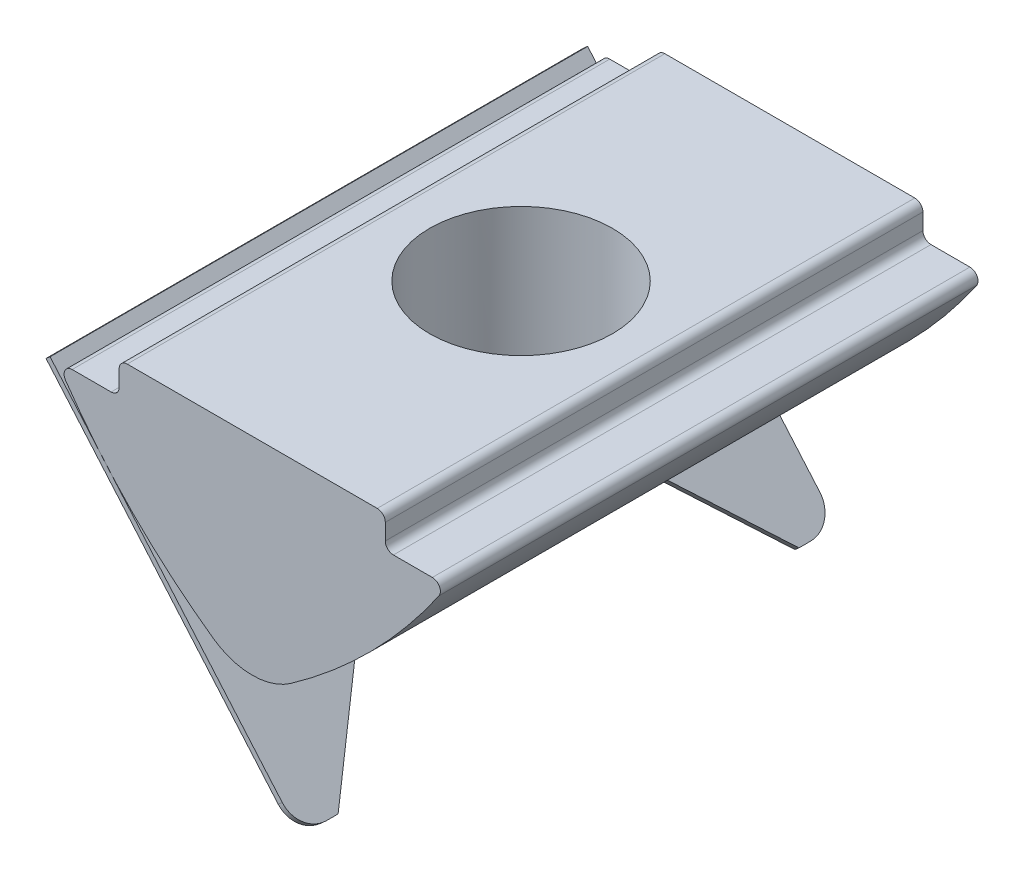
SolidWorks part; units mm, degrees
ref_plane "前视基准面" through (0, 0, 0) normal (0, 0, 1) x (1, 0, 0)
ref_plane "上视基准面" through (0, 0, 0) normal (0, 1, 0) x (1, 0, 0)
ref_plane "右视基准面" through (0, 0, 0) normal (1, 0, 0) x (0, 0, -1)
sketch "草图1" plane through (0, 0, 0) normal (0, 0, 1) x (1, 0, 0)
  line B0 (-4.95, -0.3) -> (-4.95, -0.9)
  line B1 (4.95, -0.3) -> (4.95, -0.9)
  line B2 (4.65, 0) -> (-4.65, 0)
  line B3 (-5.25, -1.2) -> (-6.7, -1.2)
  line B4 (5.25, -1.2) -> (6.7, -1.2)
  arc B5 (4.95, -0.3) -> (4.65, 0) centre (4.65, -0.3) ccw
  arc B6 (-4.65, 0) -> (-4.95, -0.3) centre (-4.65, -0.3) ccw
  arc B7 (-5.25, -1.2) -> (-4.95, -0.9) centre (-5.25, -0.9) ccw
  arc B8 (4.95, -0.9) -> (5.25, -1.2) centre (5.25, -0.9) ccw
  arc B9 (-1.4566, -7.2318) -> (1.4566, -7.2318) centre (0, -5.2) ccw
  arc B10 (1.4276, -7.2523) -> (6.9516, -1.6634) centre (-11.418, 10.9685) ccw
  arc B11 (6.9516, -1.6634) -> (6.7, -1.2) centre (6.7, -1.5) ccw
  arc B12 (-6.9516, -1.6634) -> (-1.4276, -7.2523) centre (11.418, 10.9685) ccw
  arc B13 (-6.7, -1.2) -> (-6.9516, -1.6634) centre (-6.7, -1.5) ccw
sketch_block_instance "A$C525F5C17-1"
sketch_block "A$C525F5C17"
extrude "凸台-拉伸1" add sketch "草图1" along normal mid plane 20 contours B3 B13 B12 B9 B10 B11 B4 B8 B1 B5 B2 B6 B0 B7
sketch "草图3" plane through (0, 0, 0) normal (0, 1, 0) x (1, 0, 0)
  point P0 (0, 0)
hole_wizard "M8 螺纹孔1" positions "3D草图2" profile "草图4" tap size "M8" standard "Iso"
sketch3d "3D草图2"
  point P0 (0, 0, 0)
sketch "草图4" plane through (0, 0, 0) normal (1, 0, 0) x (0, 0, 1)
  line L0 (0, 0) -> (0, 21.7929)
  line L1 (0, 21.7929) -> (3.4, 19.75)
  line L2 (3.4, 19.75) -> (3.4, 0)
  line L5 (3.4, 0) -> (0, 0)
  line L10 (0, 21.7929) -> (-3.4, 19.75) construction
  line L11 (0, -6.35) -> (0, 107.95) construction
  dimension "螺纹孔钻头直径" = 6.8
  dimension "螺纹孔钻头深度" = 19.75
  dimension "导头角度" = 118
cosmetic thread "孔螺蚊线1" parameters "D1"=7.7, "D2"=8
sketch "草图5" plane through (0, 0, 10) normal (0, 0, 1) x (1, 0, 0)
  line L0 (-7.5212, -1.2) -> (1.7673, -12)
  line L1 (4.65, 0) -> (-4.65, 0) construction
  line L2 (-7.6728, -1.3304) -> (1.6157, -12.1304)
  line L4 (-7.5212, -1.2) -> (-7.6728, -1.3304)
  line L5 (1.7673, -12) -> (1.6157, -12.1304)
  arc A1 (-6.9516, -1.6634) -> (-1.4276, -7.2523) centre (11.418, 10.9685) ccw construction
  dimension "D1" = 12
  dimension "D2" = 0.2
extrude "凸台-拉伸2" add sketch "草图5" against normal blind 20 separate body
sketch "草图6" plane through (-5.0682, -4.3589, 0) normal (-0.7582, -0.6521, 0) x (0, 0, 1)
  line L0 (-1.5674, -3.0135) -> (1.5674, -3.0135)
  line L1 (0, 0) -> (0, -3.0135) construction
  line L2 (3.0995, -3.7279) -> (8.5725, -10.2504)
  line L3 (-10, -10.2504) -> (10, -10.2504) construction
  line L4 (8.5725, -10.2504) -> (9, -10.2504)
  line L5 (10, -9.2504) -> (10, -6.703)
  line L6 (-10, -9.2504) -> (-10, -6.703)
  line L7 (-8.5725, -10.2504) -> (-9, -10.2504)
  line L8 (-3.0995, -3.7279) -> (-8.5725, -10.2504)
  line L9 (10, -6.703) -> (14.4576, -13.4188)
  line L10 (14.4576, -13.4188) -> (-1.0667, -21.0252)
  line L11 (-1.0667, -21.0252) -> (-16.3104, -17.222)
  line L12 (-16.3104, -17.222) -> (-10, -6.703)
  arc A0 (10, -9.2504) -> (9, -10.2504) centre (9, -9.2504) cw
  arc A1 (-3.0995, -3.7279) -> (-1.5674, -3.0135) centre (-1.5674, -5.0135) cw
  arc A2 (3.0995, -3.7279) -> (1.5674, -3.0135) centre (1.5674, -5.0135) ccw
  arc A3 (-10, -9.2504) -> (-9, -10.2504) centre (-9, -9.2504) ccw
  point P16 (-10, -10.2504)
  point P19 (-2.5, -3.0135)
  point P22 (2.5, -3.0135)
  point P25 (10, -10.2504)
  dimension "D3" = 1
  dimension "D1" = 5
  dimension "D2" = 130
extrude "切除-拉伸1" cut sketch "草图6" against normal blind 0.2
